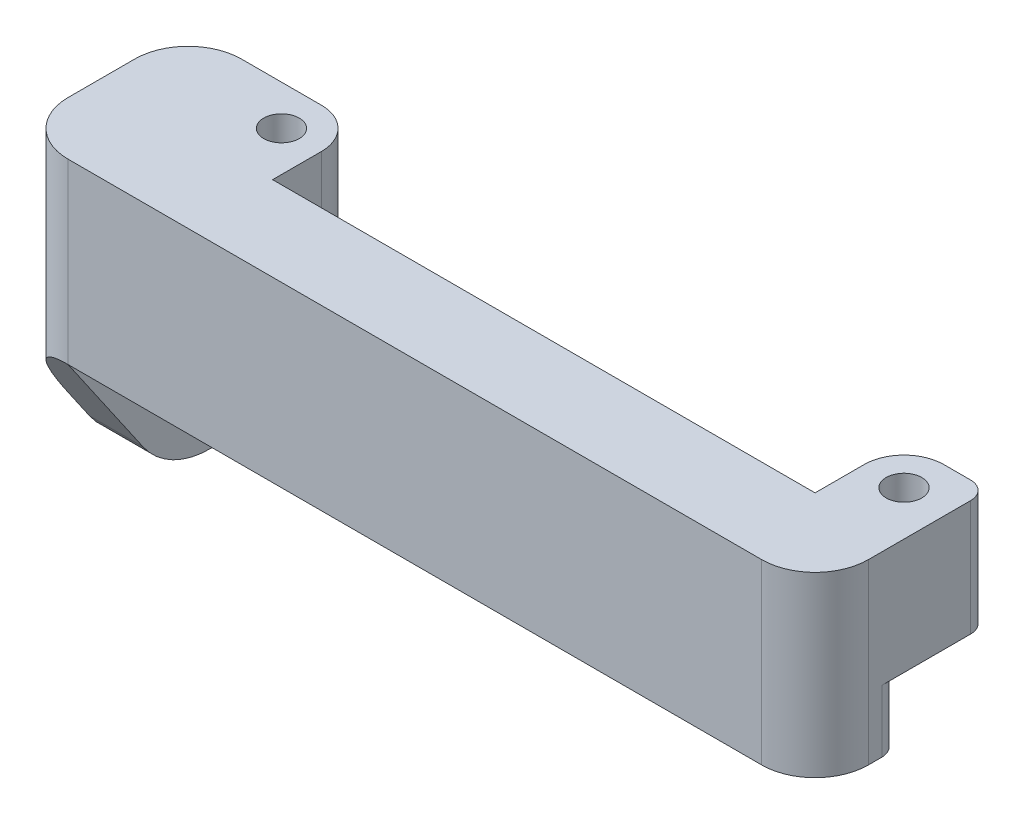
SolidWorks part; units mm, degrees
ref_plane "Front Plane" through (0, 0, 0) normal (0, 0, 1) x (1, 0, 0)
ref_plane "Top Plane" through (0, 0, 0) normal (0, 1, 0) x (1, 0, 0)
ref_plane "Right Plane" through (0, 0, 0) normal (1, 0, 0) x (0, 0, -1)
ref_plane "Plane1" through (-25, 0, 0) normal (-1, 0, 0) x (0, -1, 0)
sketch "Sketch1" plane through (-25, 0, 0) normal (-1, 0, 0) x (0, -1, 0)
  line L0 (-6.5, -2.25) -> (0, -2.25)
  line L1 (0, -2.25) -> (5.0145, -4.6494)
  line L2 (9.6109, 3.2873) -> (3.5, 7.5)
  line L3 (3.5, 7.5) -> (-6.5, 7.5)
  line L4 (-6.5, 7.5) -> (-6.5, -2.25)
  arc A0 (5.0145, -4.6494) -> (9.6109, 3.2873) centre (7, -0.5) ccw
extrude "Boss-Extrude1" add sketch "Sketch1" against normal blind 3
sketch "Sketch2" plane through (-22, 0, 0) normal (1, 0, 0) x (0, 0, -1)
  line L0 (2.25, -3.5) -> (-7.5, -3.5)
  line L1 (-7.5, -3.5) -> (-7.5, 6.5)
  line L2 (-7.5, 6.5) -> (2.25, 6.5)
  line L3 (2.25, 6.5) -> (2.25, -3.5)
extrude "Boss-Extrude2" add sketch "Sketch2" along normal blind 6.75
sketch "Sketch3" plane through (0, 0, -2.25) normal (0, 0, -1) x (-1, 0, 0)
  line L0 (15.25, 0) -> (15.25, -3.5)
  line L1 (15.25, -3.5) -> (22, -3.5)
  line L2 (22, -3.5) -> (22, 0)
  line L3 (22, 0) -> (15.25, 0)
extrude "Cut-Extrude1" cut sketch "Sketch3" against normal blind 5
sketch "Sketch4" plane through (-15.25, 0, 0) normal (1, 0, 0) x (0, 0, -1)
  line L0 (-2.75, 6.5) -> (-2.75, -3.5)
  line L1 (-2.75, -3.5) -> (-7.5, -3.5)
  line L2 (-7.5, -3.5) -> (-7.5, 6.5)
  line L3 (-7.5, 6.5) -> (-2.75, 6.5)
extrude "Boss-Extrude3" add sketch "Sketch4" along normal blind 35.25
sketch "Sketch5" plane through (0, 0, 2.75) normal (0, 0, -1) x (-1, 0, 0)
  line L0 (-15.25, 0) -> (-20, 0)
  line L1 (-20, 0) -> (-20, 6.5)
  line L2 (-20, 6.5) -> (-15.25, 6.5)
  line L3 (-15.25, 6.5) -> (-15.25, 0)
extrude "Boss-Extrude4" add sketch "Sketch5" along normal blind 5
hole_wizard "Ø2.0 (2) Diameter Hole1" positions "Sketch7" profile "Sketch6" hole size "Ø2.0" standard "ANSI Metric"
sketch "Sketch7" plane through (0, 0, 0) normal (0, -1, 0) x (-1, 0, 0)
  point P0 (-17.5, 0)
  point P1 (17.5, 0)
sketch "Sketch6" plane through (17.5, 0, 0) normal (1, 0, 0) x (0, 0, -1)
  line L0 (0, 0) -> (0, 6.5)
  line L1 (0, 6.5) -> (1, 6.5)
  line L2 (1, 6.5) -> (1, 0)
  line L5 (1, 0) -> (0, 0)
  line L11 (0, -6.35) -> (0, 107.95) construction
  dimension "Thru Hole Dia." = 2
  dimension "Thru Hole Depth" = 6.5
hole_wizard "Ø3.2 (3.2) Diameter Hole1" positions "Sketch9" profile "Sketch8" hole size "Ø3.2" standard "ANSI Metric"
sketch "Sketch9" plane through (-22, 0, 0) normal (1, 0, 0) x (0, 0, -1)
  point P0 (0.5, -7)
sketch "Sketch8" plane through (-22, -7, -0.5) normal (0, 1, 0) x (0, 0, -1)
  line L0 (0, 0) -> (0, 3)
  line L1 (0, 3) -> (1.6, 3)
  line L2 (1.6, 3) -> (1.6, 0)
  line L5 (1.6, 0) -> (0, 0)
  line L11 (0, -6.35) -> (0, 107.95) construction
  dimension "Thru Hole Dia." = 3.2
  dimension "Thru Hole Depth" = 3
fillet "Fillet1" radius 1 2 edges at (20, -1.75, 2.75) (20, 3.25, -2.25)
fillet "Fillet2" radius 2.25 2 edges at (15.25, 3.25, -2.25) (-15.25, 3.25, -2.25)
fillet "Fillet3" radius 3 3 edges at (20, 1.5, 7.5) (-25, 3.25, -2.25) (-25, 1.5, 7.5)
